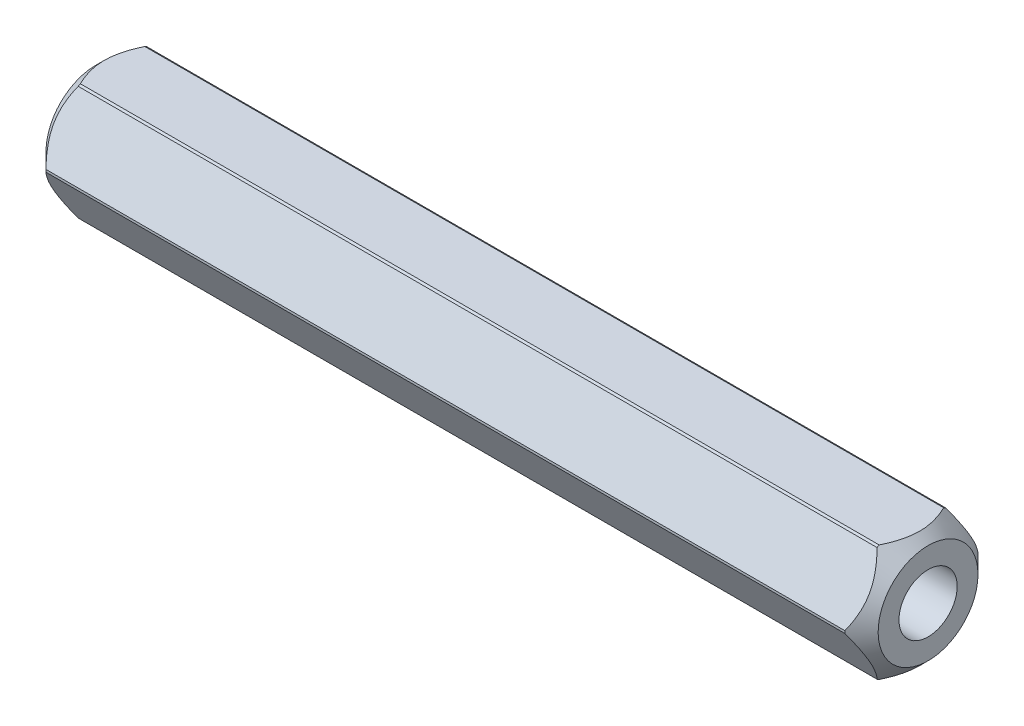
SolidWorks part; units mm, degrees
material "6061-O (SS)"
ref_plane "前视基准面" through (0, 0, 0) normal (0, 0, 1) x (1, 0, 0)
ref_plane "上视基准面" through (0, 0, 0) normal (0, 1, 0) x (1, 0, 0)
ref_plane "右视基准面" through (0, 0, 0) normal (1, 0, 0) x (0, 0, -1)
sketch "草图1" plane through (0, 0, 0) normal (1, 0, 0) x (0, 0, -1)
  line L1 (4.0415, 0) -> (2.0207, 3.5)
  line L2 (2.0207, 3.5) -> (-2.0207, 3.5)
  line L3 (-2.0207, 3.5) -> (-4.0415, 0)
  line L4 (-4.0415, 0) -> (-2.0207, -3.5)
  line L5 (-2.0207, -3.5) -> (2.0207, -3.5)
  line L6 (2.0207, -3.5) -> (4.0415, 0)
  circle A1 centre (0, 0) radius 3.5 construction
  dimension "D1" = 7
extrude "初始整轴" add sketch "草图1" along normal mid plane 50
sketch "草图8" plane through (0, 0, 0) normal (1, 0, 0) x (0, 0, -1)
  circle A0 centre (0, 0) radius 4
  circle A1 centre (0, 0) radius 5
  dimension "D1" = 8
  dimension "D2" = 1
extrude "整轴外圆" cut sketch "草图8" against normal through all both and the other way through all
sketch "草图9" plane through (0, 0, 0) normal (1, 0, 0) x (0, 0, -1)
  circle A0 centre (0, 0) radius 1.75
  dimension "D1" = 3.5
extrude "中心孔切除" cut sketch "草图9" against normal through all both and the other way through all
sketch "草图10" plane through (0, 0, 0) normal (0, 0, 1) x (1, 0, 0)
  line L0 (25, 0) -> (-25, 0) construction
  line L7 (0, 0) -> (0, 3.4271) construction
  line L8 (-25, 3.4271) -> (25, 3.4271) construction
  line L12 (-25.5, 4) -> (-24, 4)
  line L13 (-25.5, 4) -> (-25.5, 2.5)
  line L14 (-24, 4) -> (-25.5, 2.5)
  line L15 (-25, 3.4271) -> (-25, 0.0729) construction
  line L16 (25, 3.5) -> (-25, 3.5) construction
  line L17 (24, 4) -> (25.5, 2.5)
  line L18 (25.5, 4) -> (25.5, 2.5)
  line L19 (25.5, 4) -> (24, 4)
  line L20 (-25, 0.0729) -> (-25, -0.0729) construction
  point P6 (0, 0)
  point P8 (0, 0)
  dimension "D1" = 1.5
  dimension "D2" = 1.5
  dimension "D3" = 0.5
  dimension "D4" = 0.5
revolve "初始倒角" cut sketch "草图10" angle 360 about L0
sketch "草图2" [suppressed] plane through (25, 0, 0) normal (1, 0, 0) x (0, 0, -1)
  circle A0 centre (0, 0) radius 3
  circle A1 centre (0, 0) radius 4
  dimension "D1" = 8
  dimension "右侧凸台直径" = 6
extrude "右侧凸台切除" [suppressed] cut sketch "草图2" against normal blind 5
chamfer "右侧凸台倒角" [suppressed] distance 0.3 angle 45
sketch "草图3" [suppressed] plane through (-25, 0, 0) normal (-1, 0, 0) x (0, 0, 1)
  circle A0 centre (0, 0) radius 3
  circle A1 centre (0, 0) radius 4
  dimension "D1" = 8
  dimension "左侧凸台直径" = 6
extrude "左侧凸台切除" [suppressed] cut sketch "草图3" against normal blind 5
chamfer "左侧凸台倒角" [suppressed] distance 0.3 angle 45
sketch "草图4" plane through (0, 0, 0) normal (0, 0, 1) x (1, 0, 0)
  line L0 (-13.3489, 0) -> (13.3489, 0) construction
  line L3 (14.5, 4) -> (15.5, 4)
  line L4 (14.5, 4) -> (14.5, 3.3)
  line L5 (14.5, 3.3) -> (15.5, 3.3)
  line L6 (15.5, 4) -> (15.5, 3.3)
  line L7 (15, 4) -> (15, -2.1923) construction
  point P6 (0, 0)
  dimension "D1" = 3.3
  dimension "D2" = 4
  dimension "槽1宽度" = 1
  dimension "槽1中心距离" = 15
revolve "卡簧槽1" [suppressed] cut sketch "草图4" angle 360 about L0
sketch "草图5" plane through (0, 0, 0) normal (0, 0, 1) x (1, 0, 0)
  line L0 (-10.9541, 0) -> (10.9541, 0) construction
  line L3 (-15.5, 4) -> (-14.5, 4)
  line L4 (-15.5, 4) -> (-15.5, 3.3)
  line L5 (-15.5, 3.3) -> (-14.5, 3.3)
  line L6 (-14.5, 4) -> (-14.5, 3.3)
  line L7 (-15, 4) -> (-15, -2.3192) construction
  point P6 (0, 0)
  dimension "D1" = 3.3
  dimension "D2" = 4
  dimension "槽2宽度" = 1
  dimension "槽2中心距离" = 15
revolve "卡簧槽2" [suppressed] cut sketch "草图5" angle 360 about L0
sketch "草图6" [suppressed] plane through (25, 0, 0) normal (1, 0, 0) x (0, 0, -1)
  circle A0 centre (0, 0) radius 2
  dimension "右侧攻丝直径" = 4
extrude "右侧攻丝切除" [suppressed] cut sketch "草图6" against normal blind 5
chamfer "右侧攻丝倒角" [suppressed] distance 0.5 angle 45
sketch "草图7" [suppressed] plane through (-25, 0, 0) normal (-1, 0, 0) x (0, 0, 1)
  circle A0 centre (0, 0) radius 2
  dimension "左侧攻丝直径" = 4
extrude "左侧攻丝切除" [suppressed] cut sketch "草图7" against normal blind 5
chamfer "左侧攻丝倒角" [suppressed] distance 0.5 angle 45
other "冻结***"
